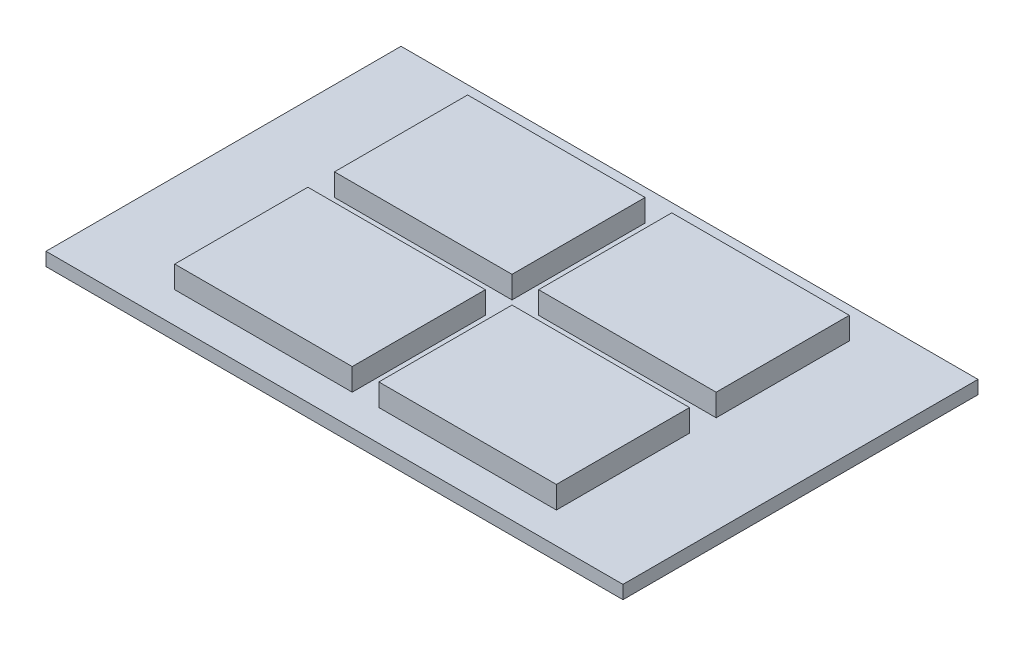
SolidWorks part; units mm, degrees
ref_plane "Front Plane" through (0, 0, 0) normal (0, 0, 1) x (1, 0, 0)
ref_plane "Top Plane" through (0, 0, 0) normal (0, 1, 0) x (1, 0, 0)
ref_plane "Right Plane" through (0, 0, 0) normal (1, 0, 0) x (0, 0, -1)
sketch "Sketch1" plane through (0, 0, 0) normal (0, 1, 0) x (1, 0, 0)
  line L1 (65, 40) -> (-65, 40)
  line L2 (65, 40) -> (65, -40)
  line L3 (65, -40) -> (-65, -40)
  line L4 (-65, 40) -> (-65, -40)
  line L5 (65, 40) -> (-65, -40) construction
  line L6 (65, -40) -> (-65, 40) construction
  point P0 (0, 0)
  dimension "D1" = 130
  dimension "D2" = 80
extrude "Boss-Extrude1" add sketch "Sketch1" along normal blind 3
sketch "Sketch2" plane through (0, 3, 0) normal (0, 1, 0) x (1, 0, 0)
  line L0 (0, 40) -> (0, -40) construction
  line L1 (-43, 33) -> (-3, 33)
  line L2 (-43, 33) -> (-43, 3)
  line L3 (-43, 3) -> (-3, 3)
  line L4 (-3, 33) -> (-3, 3)
  line L5 (-43, 33) -> (-3, 3) construction
  line L6 (-43, 3) -> (-3, 33) construction
  line L7 (65, 40) -> (-65, 40) construction
  line L8 (-65, -40) -> (65, -40) construction
  line L9 (-65, 0) -> (65, 0) construction
  line L10 (-65, 40) -> (-65, -40) construction
  line L11 (65, -40) -> (65, 40) construction
  line L12 (43, 3) -> (3, 3)
  line L13 (3, 33) -> (3, 3)
  line L14 (43, 33) -> (3, 33)
  line L15 (43, 33) -> (43, 3)
  line L16 (43, -3) -> (3, -3)
  line L17 (43, -33) -> (43, -3)
  line L18 (43, -33) -> (3, -33)
  line L19 (3, -33) -> (3, -3)
  line L20 (-3, -33) -> (-3, -3)
  line L21 (-43, -3) -> (-3, -3)
  line L22 (-43, -33) -> (-43, -3)
  line L23 (-43, -33) -> (-3, -33)
  point P0 (-23, 18)
  dimension "D1" = 40
  dimension "D2" = 30
  dimension "D3" = 3
  dimension "D4" = 3
extrude "Boss-Extrude2" add sketch "Sketch2" along normal blind 5
